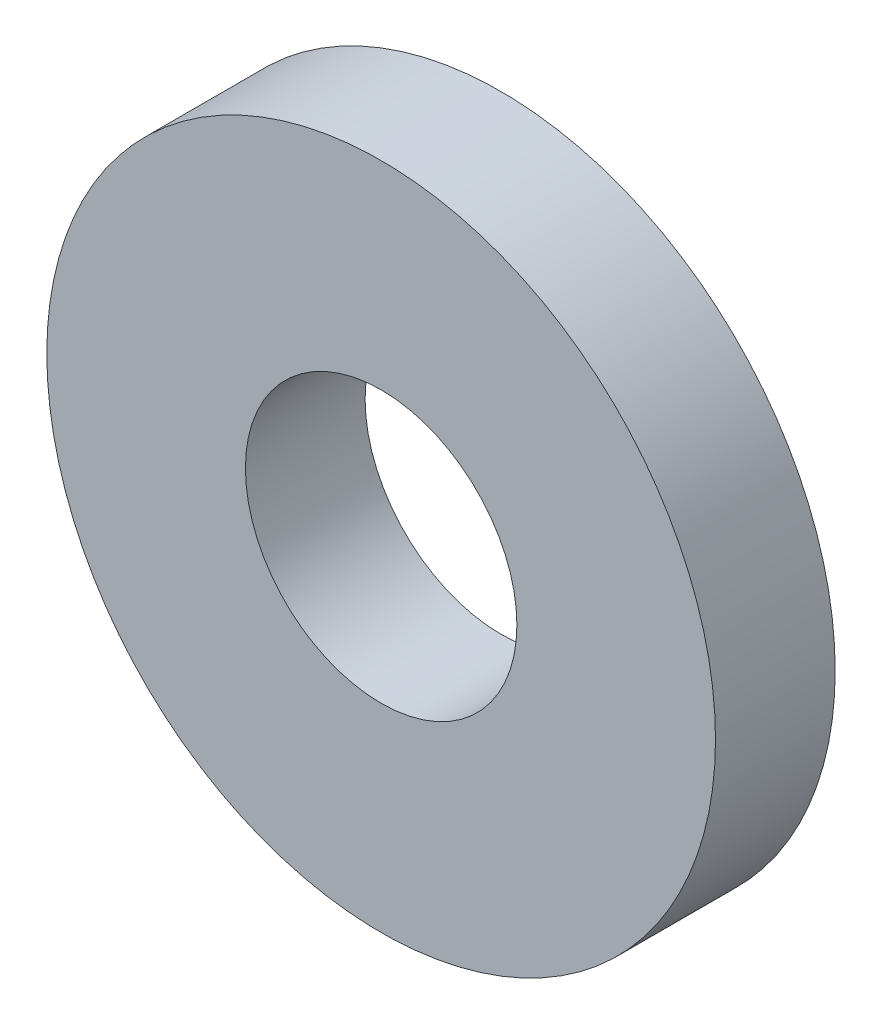
SolidWorks part; units mm, degrees
ref_plane "Front Plane" through (0, 0, 0) normal (0, 0, 1) x (1, 0, 0)
ref_plane "Top Plane" through (0, 0, 0) normal (0, 1, 0) x (1, 0, 0)
ref_plane "Right Plane" through (0, 0, 0) normal (1, 0, 0) x (0, 0, -1)
sketch "Sketch1" plane through (0, 0, 0) normal (1, 0, 0) x (0, 0, -1)
  line L0 (0, -2.5781) -> (0, 2.5781) construction
  line L1 (0, -6.35) -> (0, 6.35) construction
  line L2 (-1.1366, 6.35) -> (1.1367, 6.35)
  point P4 (0, 0)
  point P8 (0, 0)
  point P10 (0, 6.35)
  dimension "Thickness" = 2.2733
sketch "Sketch2" plane through (0, 0, 0) normal (0, 0, 1) x (1, 0, 0)
  line L1 (0, -2.5781) -> (0, 2.5781) construction
  circle A2 centre (0, 0) radius 2.5781
  circle A3 centre (0, 0) radius 6.35
  point P3 (0, 0)
  dimension "D1" = 5.1562
  dimension "D2" = 12.7
extrude "Boss-Extrude1" add sketch "Sketch2" along normal mid plane 2.2733
equation "\"D1@Boss-Extrude1\"=\"Thickness@Sketch1\""
equation "\"D1@Sketch2\"=\"ID@Sketch1\""
equation "\"D2@Sketch2\"=\"OD@Sketch1\""
